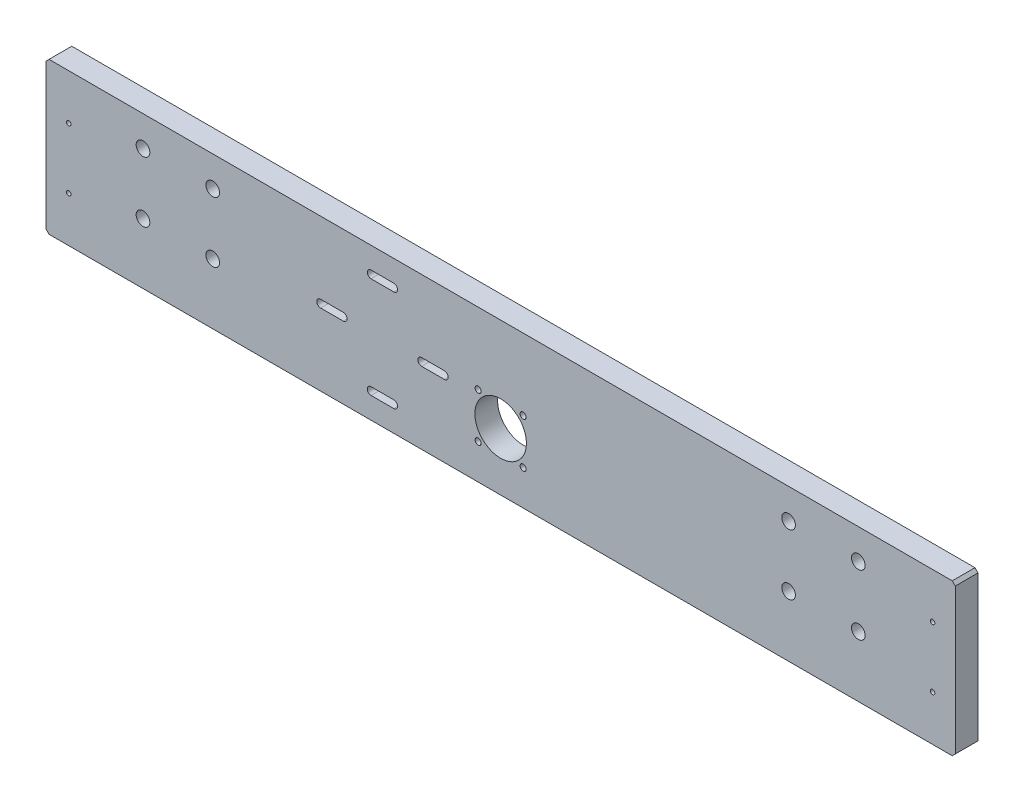
SolidWorks part; units mm, degrees
ref_plane "Piano frontale" through (0, 0, 0) normal (0, 0, 1) x (1, 0, 0)
ref_plane "Piano superiore" through (0, 0, 0) normal (0, 1, 0) x (1, 0, 0)
ref_plane "Piano destro" through (0, 0, 0) normal (1, 0, 0) x (0, 0, -1)
sketch "Schizzo1" plane through (0, 0, 0) normal (0, 0, 1) x (1, 0, 0)
  line L0 (300, 100) -> (300, 0) construction
  line L1 (2, 0) -> (598, 0)
  line L2 (0, 2) -> (0, 98)
  line L3 (2, 100) -> (598, 100)
  line L4 (600, 2) -> (600, 98)
  line L5 (87, 100) -> (87, 0) construction
  line L6 (384.4715, 38) -> (198.6179, 38) construction
  line L7 (300, 38) -> (318.5099, 38) construction
  line L9 (300, 38) -> (280.51, 57.49) construction
  line L21 (0, 98) -> (2, 100)
  line L22 (2, 0) -> (0, 2)
  line L23 (598, 0) -> (600, 2)
  line L24 (598, 100) -> (600, 98)
  circle A0 centre (300, 38) radius 17
  circle A1 centre (300, 38) radius 21 construction
  circle A2 centre (314.8492, 52.8492) radius 2
  circle A3 centre (314.8492, 23.1508) radius 2
  circle A4 centre (285.1508, 23.1508) radius 2
  circle A5 centre (536, 40) radius 4.5
  circle A6 centre (536, 80) radius 4.5
  circle A7 centre (490, 40) radius 4.5
  circle A8 centre (490, 80) radius 4.5
  circle A9 centre (585, 70) radius 1.5
  circle A10 centre (585, 30) radius 1.5
  circle A11 centre (15, 30) radius 1.5
  circle A13 centre (285.1508, 52.8492) radius 2
  circle A18 centre (15, 70) radius 1.5
  circle A29 centre (110, 80) radius 4.5
  circle A30 centre (110, 40) radius 4.5
  circle A32 centre (64, 80) radius 4.5
  circle A33 centre (64, 40) radius 4.5
  point P0 (0, 0)
  point P1 (600, 100)
  point P2 (0, 100)
  point P3 (600, 0)
  point P9 (285.1508, 52.8492)
  point P13 (285.1508, 52.8492)
  dimension "D4" = 34
  dimension "D10" = 23
  dimension "D15" = 3
  dimension "D17" = 4
  dimension "D8" = 45
  dimension "D5" = 42
  dimension "D9" = 64
  dimension "D11" = 9
  dimension "D1" = 100
  dimension "D2" = 600
  dimension "D3" = 38
  dimension "D6" = 20
  dimension "D7" = 40
  dimension "D14" = 30
  dimension "D16" = 15
extrude "Boss-Extrude1" add sketch "Schizzo1" against normal blind 15
sketch "Sketch2" plane through (0, 0, 0) normal (0, -1, 0) x (1, 0, 0)
  line L0 (2, -7.5) -> (598, -7.5) construction
  line L1 (2, -15) -> (2, 0) construction
  line L2 (598, -15) -> (598, 0) construction
  line L3 (300, -15) -> (300, 0) construction
  line L4 (2, -15) -> (598, -15) construction
  line L5 (321, 0) -> (279, 0) construction
  line L6 (0, -15) -> (0, 0) construction
  point P12 (30, -7.5)
  point P15 (570, -7.5)
  dimension "D1" = 30
hole_wizard "M8 Tapped Hole1" positions "3DSketch1" profile "Sketch3" tap size "M8" standard "ISO"
sketch3d "3DSketch1"
  point P0 (30, 0, -7.5)
  point P3 (570, 0, -7.5)
sketch "Sketch3" plane through (30, 0, -7.5) normal (1, 0, 0) x (0, 0, -1)
  line L0 (0, 0) -> (0, 25.7929)
  line L1 (0, 25.7929) -> (3.4, 23.75)
  line L2 (3.4, 23.75) -> (3.4, 0)
  line L5 (3.4, 0) -> (0, 0)
  line L10 (0, 25.7929) -> (-3.4, 23.75) construction
  line L11 (0, -6.35) -> (0, 107.95) construction
  dimension "Tap Drill Dia." = 6.8
  dimension "Tap Drill Depth" = 23.75
  dimension "Drill Angle" = 118
sketch "Sketch7" plane through (0, 0, -15) normal (0, 0, -1) x (-1, 0, 0)
  line L0 (-214.5, 83.333) -> (-229.5, 83.333) construction
  line L1 (-214.5, 80.833) -> (-229.5, 80.833)
  line L2 (-214.5, 85.833) -> (-229.5, 85.833)
  line L3 (-247.833, 50) -> (-262.833, 50) construction
  line L4 (-247.833, 47.5) -> (-262.833, 47.5)
  line L5 (-247.833, 52.5) -> (-262.833, 52.5)
  line L6 (-181.173, 50) -> (-196.173, 50) construction
  line L7 (-181.173, 47.5) -> (-196.173, 47.5)
  line L8 (-181.173, 52.5) -> (-196.173, 52.5)
  line L9 (-214.5, 16.673) -> (-229.5, 16.673) construction
  line L10 (-214.5, 14.173) -> (-229.5, 14.173)
  line L11 (-214.5, 19.173) -> (-229.5, 19.173)
  arc A0 (-214.5, 80.833) -> (-214.5, 85.833) centre (-214.5, 83.333) ccw
  arc A1 (-229.5, 85.833) -> (-229.5, 80.833) centre (-229.5, 83.333) ccw
  arc A2 (-247.833, 47.5) -> (-247.833, 52.5) centre (-247.833, 50) ccw
  arc A3 (-262.833, 52.5) -> (-262.833, 47.5) centre (-262.833, 50) ccw
  arc A4 (-181.173, 47.5) -> (-181.173, 52.5) centre (-181.173, 50) ccw
  arc A5 (-196.173, 52.5) -> (-196.173, 47.5) centre (-196.173, 50) ccw
  arc A6 (-214.5, 14.173) -> (-214.5, 19.173) centre (-214.5, 16.673) ccw
  arc A7 (-229.5, 19.173) -> (-229.5, 14.173) centre (-229.5, 16.673) ccw
  point P0 (-255.333, 50)
  point P1 (-222, 83.333)
  point P2 (-188.673, 50)
  point P3 (-222, 16.673)
  point P6 (-222, 83.333)
  point P13 (-255.333, 50)
  point P20 (-188.673, 50)
  point P27 (-222, 16.673)
extrude "Cut-Extrude1" cut sketch "Sketch7" against normal through all
